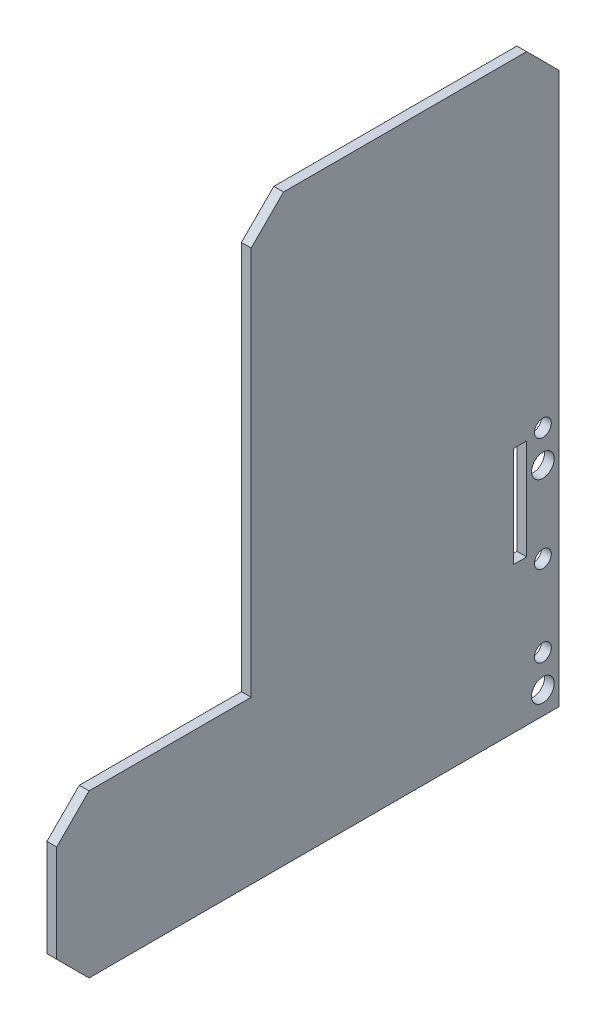
SolidWorks part; units mm, degrees
material "Alliage 1060"
ref_plane "Plan de face" through (0, 0, 0) normal (0, 0, 1) x (1, 0, 0)
ref_plane "Plan de dessus" through (0, 0, 0) normal (0, 1, 0) x (1, 0, 0)
ref_plane "Plan de droite" through (0, 0, 0) normal (1, 0, 0) x (0, 0, -1)
sketch "Esquisse1" plane through (0, 0, 0) normal (1, 0, 0) x (0, 0, -1)
  line L1 (2.5, 69) -> (-75, 69)
  line L2 (2.5, 69) -> (2.5, -21)
  line L3 (2.5, -21) -> (-75, -21)
  line L4 (-75, 69) -> (-75, -21)
  circle A0 centre (0, 12.5) radius 1.5 construction
  circle A1 centre (0, -17.5) radius 1.5 construction
  circle A2 centre (0, -17.5) radius 1.75
  circle A3 centre (0, 12.5) radius 1.75
  dimension "D2" = 3.5
  dimension "D1" = 75
  dimension "D3" = 90
extrude "Extrusion1" add sketch "Esquisse1" along normal blind 1.5
hole_wizard "Fraisage pour vis à tête fraisée M2.51" positions "Esquisse4" profile "Esquisse3" hole size "#0000" standard "Ansi Pouces" end condition through all
sketch "Esquisse4" plane through (1.5, 0, 0) normal (1, 0, 0) x (0, 0, -1)
  line L0 (2.5, 16) -> (-2.5, 16) construction
  line L1 (2.5, -14) -> (-2.5, -14) construction
  point P0 (0, 17.5)
  point P1 (0, -12.5)
  point P5 (0, 0)
  dimension "D2" = 1.5
  dimension "D1" = 1.5
sketch "Esquisse3" plane through (1.5, 17.5, 0) normal (0, 1, 0) x (0, 0, -1)
  line L0 (0, 0) -> (0, 1.5)
  line L1 (0, 1.5) -> (1.3, 1.5)
  line L2 (1.3, 1.5) -> (1.3, 0)
  line L5 (1.3, 0) -> (0, 0)
  line L11 (0, -6.35) -> (0, 107.95) construction
  dimension "Diamètre du perçage jusqu'au prochain" = 2.6
  dimension "Profondeur du perçage jusqu'au prochain" = 1.5
sketch "Esquisse5" plane through (0, 0, 0) normal (-1, 0, 0) x (0, 0, 1)
  line L1 (2.5, 17) -> (4.5, 17)
  line L2 (2.5, 17) -> (2.5, 1.5)
  line L3 (2.5, 1.5) -> (4.5, 1.5)
  line L4 (4.5, 17) -> (4.5, 1.5)
  line L5 (2.5, -21) -> (2.5, 21) construction
  dimension "D1" = 2
  dimension "D2" = 17
  dimension "D3" = 1.5
extrude "Enlèv. mat.-Extru.1" cut sketch "Esquisse5" against normal through all
sketch "Esquisse6" plane through (1.5, 0, 0) normal (1, 0, 0) x (0, 0, -1)
  line L0 (-75, 69) -> (-75, -1)
  line L1 (-75, 69) -> (-75, -21) construction
  line L2 (-70, 4) -> (-45, 4)
  line L3 (-45, 4) -> (-45, 64)
  line L4 (-45, 64) -> (-40, 69)
  line L5 (2.5, 69) -> (-75, 69) construction
  line L6 (-40, 69) -> (-75, 69)
  line L7 (-75, -21) -> (2.5, -21) construction
  line L8 (-70, 4) -> (-75, -1)
  line L9 (-75, -21) -> (-70, -21)
  line L10 (-70, -21) -> (-75, -16)
  line L11 (-75, -16) -> (-75, -21)
  line L12 (2.5, 69) -> (2.5, 64)
  line L13 (2.5, 64) -> (-2.5, 69)
  line L14 (-2.5, 69) -> (2.5, 69)
  dimension "D1" = 45
  dimension "D2" = 30
  dimension "D3" = 25
  dimension "D4" = 5
  dimension "D5" = 5
  dimension "D6" = 5
  dimension "D7" = 5
  dimension "D8" = 5
  dimension "D9" = 5
extrude "Enlèv. mat.-Extru.2" cut sketch "Esquisse6" against normal up to next
